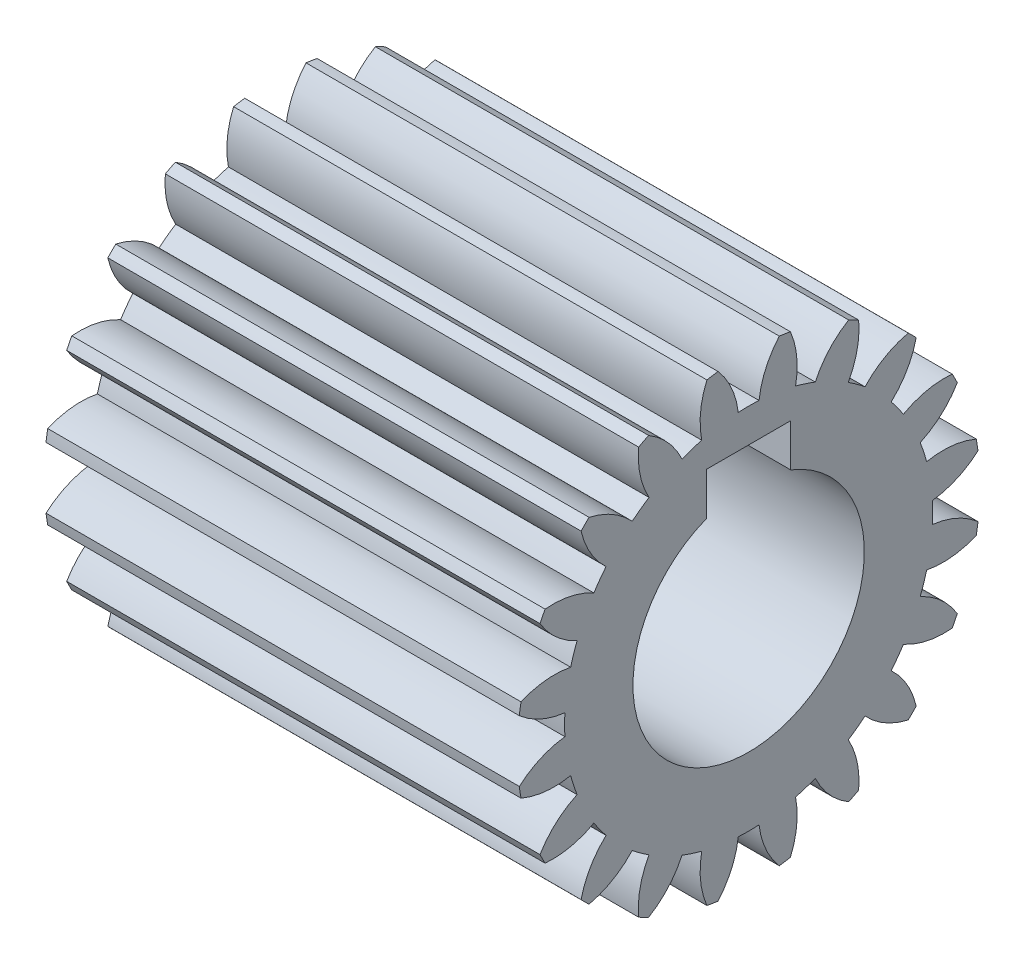
SolidWorks part; units mm, degrees
ref_plane "Plane1" through (0, 0, 0) normal (0, 0, 1) x (1, 0, 0)
ref_plane "Plane2" through (0, 0, 0) normal (0, 1, 0) x (1, 0, 0)
ref_plane "Plane3" through (0, 0, 0) normal (1, 0, 0) x (0, 0, -1)
sketch "HoldingSke" plane through (0, 0, 0) normal (0, 1, 0) x (1, 0, 0)
  line L0 (0, 0) -> (0.4698, -0.171)
  line L1 (-15, 0) -> (100, 0) construction
  line L2 (0, 0) -> (-2.1039, 2.3779)
  line L3 (0, 0) -> (-11.863, 4.5341)
  line L4 (0, 0) -> (8.1152, 2.9537)
  line L5 (0, 0) -> (-46.8476, -17.4728)
  line L6 (0, 0) -> (-37.3033, -25.1687)
  line L7 (-2.1039, 2.3779) -> (8.6586, 51.2059)
  line L8 (-76.2, 54.61) -> (-72.9, 54.61)
  line L9 (-71.009, 38.7566) -> (-53.1078, 45.2721)
  line L10 (-76.2, 71.12) -> (104.1128, 71.12)
  line L11 (0, 0) -> (-45, 0)
  line L12 (-76.2, 101.6) -> (-76.133, 101.6)
  line L13 (24.9733, 27.94) -> (52.9518, 28.4284)
  line L14 (24.9733, 27.94) -> (24.9743, 27.94)
  line L15 (24.9733, 27.94) -> (100.4006, 29.5858)
  line L16 (-63.627, -2) -> (-12.827, -2)
  circle A0 centre (0, 0) radius 11
  circle A1 centre (0, 0) radius 17.499
  circle A2 centre (0, 0) radius 37.5
  circle A3 centre (0, 0) radius 11
  dimension "MHD" = 34.998
  dimension "Hub_dia" = 75
  dimension "Bore" = 22
  dimension "MBD" = 22
  dimension "Num_teeth" = 20
  dimension "Pitch" = 0.5
  dimension "Overall_len" = 50
  dimension "Show_teeth" = 20
  dimension "Thickness" = 45
  dimension "OAL" = 50.0001
  dimension "T_dim" = 3.3
  dimension "Ap" = 20
  dimension "H" = 19.05
  dimension "Pitch_radius" = 180.3128
  dimension "Width" = 45
  dimension "Backlash" = 0.067
  dimension "Addendum_fac" = 1
  dimension "Dedendum_fac" = 1.25
  dimension "Clearance_fac" = 0.25
  dimension "Dedendum_add" = 0.001
  dimension "Module" = 2
sketch "BasProSke" plane through (0, 0, 0) normal (0, 1, 0) x (1, 0, 0)
  line L0 (-10, 0) -> (60, 0) construction
  line L1 (0, 0) -> (0, 22)
  line L2 (0, 0) -> (45, 0)
  line L3 (45, 0) -> (45, 22)
  line L4 (45, 22) -> (0, 22)
  dimension "Thickness" = 45
  dimension "Diameter" = 44
revolve "Base-Revolve" add sketch "BasProSke" angle 360 about L0
sketch "TooCutSke" plane through (0, 0, 0) normal (1, 0, 0) x (0, 0, -1)
  line L1 (0, 0) -> (0, 107) construction
  line L2 (0, 0) -> (-1.6864, 19.9288) construction
  line L3 (0, 0) -> (-6.2409, 39.4033) construction
  line L4 (-1.6864, 19.9288) -> (-3.1204, 19.7016) construction
  arc A0 (0.9862, 17.4712) -> (-0.9862, 17.4712) centre (0, 0) ccw
  arc A1 (2.9329, 21.8293) -> (-2.9329, 21.8293) centre (0, 0) ccw
  circle A2 centre (0, 0) radius 20 construction
  circle A3 centre (0, 0) radius 18.7939 construction
  arc A4 (-0.9862, 17.4712) -> (-2.9329, 21.8293) centre (-8.9313, 16.536) ccw
  arc A5 (2.9329, 21.8293) -> (0.9862, 17.4712) centre (8.9313, 16.536) ccw
  dimension "Root_dia" = 34.998
  dimension "Overcut_dia" = 44.0508
  dimension "Pitch_dia" = 40
  dimension "Base_dia" = 37.5877
  dimension "Flank_rad" = 8
  dimension "Half_ang" = 9
  dimension "Half_CT" = 1.4519
extrude "ToothCut" cut sketch "TooCutSke" along normal through all
fillet "Breaks" [suppressed] radius 0.04
fillet "RootFillets" [suppressed] radius 0.501
pattern_circular "TeethCuts" count 20 every 18 about axis through (-10, 0, 0) along (1, 0, 0) of "ToothCut", "RootFillets", "Breaks"
sketch "HubNeaOneSke" plane through (0, 0, 0) normal (-1, 0, 0) x (0, 0, 1)
  circle A0 centre (0, 0) radius 17.499
  dimension "Diameter" = 34.998
extrude "HubNearOne" [suppressed] add sketch "HubNeaOneSke" along normal blind 5.0001
sketch "HubNeaBotSke" plane through (0, 0, 0) normal (-1, 0, 0) x (0, 0, 1)
  circle A0 centre (0, 0) radius 17.499
  dimension "Diameter" = 34.998
extrude "HubNearBoth" [suppressed] add sketch "HubNeaBotSke" along normal blind 2.5
ref_plane "FarPln" through (45, 0, 0) normal (1, 0, 0) x (0, 0, -1)
sketch "HubFarSke" plane through (45, 0, 0) normal (1, 0, 0) x (0, 0, -1)
  circle A0 centre (0, 0) radius 17.499
  dimension "Diameter" = 34.998
extrude "HubFar" [suppressed] add sketch "HubFarSke" along normal blind 2.5
sketch "BorSke" plane through (0, 0, 0) normal (1, 0, 0) x (0, 0, -1)
  circle A0 centre (0, 0) radius 11
  dimension "Diameter" = 22
extrude "Bore" cut sketch "BorSke" along normal mid plane 100.0001
sketch "KeySke" plane through (0, 0, 0) normal (1, 0, 0) x (0, 0, -1)
  line L0 (-4, 0) -> (-4, 14.3)
  line L1 (-4, 14.3) -> (4, 14.3)
  line L2 (4, 14.3) -> (4, 0)
  line L3 (0, 0) -> (0, 34) construction
  line L4 (-4, 0) -> (4, 0)
  dimension "Offset" = 14.3
  dimension "Width" = 8
extrude "Keyway" cut sketch "KeySke" along normal mid plane 100.0001
pattern_circular "Keyway2" [suppressed] count 2 every 90 about axis through (-10, 0, 0) along (1, 0, 0)
equation "' \"Module@HoldingSke\" = 6.35"
equation "' \"Num_teeth@HoldingSke\" = 12"
equation "' \"Ap@HoldingSke\" =  20"
equation "' \"Ap@HoldingSke\" = 20"
equation "' \"Width@HoldingSke\" = 0.5 * 25.4"
equation "' \"Hub_dia@HoldingSke\"= 1 * 25.4"
equation "' \"Hub_dia@HoldingSke\" = 1 * 25.4"
equation "' \"Overall_len@HoldingSke\" = 1.0 * 25.4"
equation "' \"Bore@HoldingSke\" = 0.75 * 25.4"
equation "' \"T_dim@HoldingSke\" = 0.1 * 25.4"
equation "' \"Width@KeySke\" = 0.25 * 25.4"
equation "' \"Show_teeth@HoldingSke\" = 13"
equation "' \"Backlash@HoldingSke\" = 0.009 * 25.4"
equation "' \"Addendum_fac@HoldingSke\" = 1.0"
equation "' \"Dedendum_fac@HoldingSke\" = 1.25"
equation "' \"Dedendum_add@HoldingSke\" = 0.00005 * 25.4"
equation "' \"Clearance_fac@HoldingSke\" = 0.25"
equation "\"Pitch@HoldingSke\" = 1 / \"Module@HoldingSke\""
equation "\"Overcut_dia@TooCutSke\" = (\"Num_teeth@HoldingSke\" + 2 * \"Addendum_fac@HoldingSke\") / \"Pitch@HoldingSke\" + 0.002 * 25.4"
equation "\"Pitch_dia@TooCutSke\" = \"Num_teeth@HoldingSke\" / \"Pitch@HoldingSke\""
equation "\"Base_dia@TooCutSke\" = \"Num_teeth@HoldingSke\" / \"Pitch@HoldingSke\" * cos((\"Ap@HoldingSke\"  * 3.14159265 / 180))"
equation "\"Root_dia@TooCutSke\" = (\"Num_teeth@HoldingSke\" + 2) / \"Pitch@HoldingSke\" - 2 * (\"Addendum_fac@HoldingSke\" + \"Dedendum_fac@HoldingSke\") / \"Pitch@HoldingSke\" - \"Dedendum_add@HoldingSke\" * 2"
equation "\"Half_ang@TooCutSke\" = 180 / \"Num_teeth@HoldingSke\""
equation "\"Half_CT@TooCutSke\" = \"Num_teeth@HoldingSke\" / \"Pitch@HoldingSke\" * sin((3.14159265 / 2 / \"Num_teeth@HoldingSke\")) / 2 - 7 * \"Backlash@HoldingSke\" / 4"
equation "\"Flank_rad@TooCutSke\" = \"Num_teeth@HoldingSke\" / \"Pitch@HoldingSke\" / 5"
equation "\"Radius@RootFillets\" = \"Clearance_fac@HoldingSke\" / \"Pitch@HoldingSke\" + \"Dedendum_add@HoldingSke\""
equation "\"Break_rad@Breaks\" = 0.02 / \"Pitch@HoldingSke\""
equation "\"Thickness@HoldingSke\" = \"Width@HoldingSke\""
equation "\"OAL@HoldingSke\" = \"Thickness@HoldingSke\""
equation "\"MHD@HoldingSke\" = (\"Num_teeth@HoldingSke\" + 2) / \"Pitch@HoldingSke\" - 2 * (\"Addendum_fac@HoldingSke\" + \"Dedendum_fac@HoldingSke\")  / \"Pitch@HoldingSke\" - \"Dedendum_add@HoldingSke\" * 2"
equation "\"MBD@HoldingSke\" = (\"Num_teeth@HoldingSke\" + 2) / \"Pitch@HoldingSke\" - 2 * (\"Addendum_fac@HoldingSke\" + \"Dedendum_fac@HoldingSke\")  / \"Pitch@HoldingSke\" - \"Dedendum_add@HoldingSke\" * 2 - 0.002 * 25.4"
equation "\"MHD@HoldingSke\" = ((sgn( \"MHD@HoldingSke\" - \"Hub_dia@HoldingSke\" )-1)*( \"MHD@HoldingSke\" - \"Hub_dia@HoldingSke\" ))/-2+ \"Hub_dia@HoldingSke\""
equation "\"MBD@HoldingSke\" = ((sgn( \"MBD@HoldingSke\" - \"Bore@HoldingSke\" )-1)*( \"MBD@HoldingSke\" - \"Bore@HoldingSke\" ))/-2+ \"Bore@HoldingSke\""
equation "\"OAL@HoldingSke\" = ((sgn( \"OAL@HoldingSke\" - \"Overall_len@HoldingSke\" )+1)*( \"OAL@HoldingSke\" - \"Overall_len@HoldingSke\" ))/2 + \"Overall_len@HoldingSke\" + 0.000002 * 25.4"
equation "\"Num_teeth@TeethCuts\" = int( \"Show_teeth@HoldingSke\" ) + 1"
equation "\"Num_teeth@TeethCuts\" = ((sgn( \"Num_teeth@TeethCuts\" - \"Num_teeth@HoldingSke\" )-1)*( \"Num_teeth@TeethCuts\" - \"Num_teeth@HoldingSke\" ))/-2+ \"Num_teeth@HoldingSke\""
equation "\"Num_teeth@TeethCuts\" = ((sgn( \"Num_teeth@TeethCuts\" - 2.0)+1)*( \"Num_teeth@TeethCuts\" - 2.0))/2 +2.0"
equation "\"Angle@TeethCuts\" = 360.0 / \"Num_teeth@HoldingSke\""
equation "\"Diameter@BasProSke\" = (\"Num_teeth@HoldingSke\" + 2 * \"Addendum_fac@HoldingSke\") / \"Pitch@HoldingSke\""
equation "\"Thickness@BasProSke\"  = \"Thickness@HoldingSke\""
equation "' \"Fillet_rad@BasProSke\" =  \"Thickness@HoldingSke\" * 0.05"
equation "' \"Fillet_rad@BasProSke\" = \"Thickness@HoldingSke\" * 0.05"
equation "\"MHD@HoldingSke\" = ((sgn( \"MHD@HoldingSke\" - \"Root_dia@TooCutSke\" )-1)*( \"MHD@HoldingSke\" - \"Root_dia@TooCutSke\" ))/-2+ \"Root_dia@TooCutSke\""
equation "\"Diameter@HubNeaOneSke\" = \"MHD@HoldingSke\""
equation "\"Length@HubNearOne\" = \"OAL@HoldingSke\" - \"Thickness@BasProSke\""
equation "\"Diameter@HubNeaBotSke\" = \"MHD@HoldingSke\""
equation "\"Length@HubNearBoth\" = ( \"OAL@HoldingSke\" - \"Thickness@BasProSke\" ) / 2.0"
equation "\"Thickness@FarPln\" = \"Thickness@BasProSke\""
equation "\"Diameter@HubFarSke\" = \"MHD@HoldingSke\""
equation "\"Length@HubFar\" = ( \"OAL@HoldingSke\" - \"Thickness@BasProSke\" ) / 2.0"
equation "\"Diameter@BorSke\" = \"MBD@HoldingSke\""
equation "\"D1@Bore\" = \"OAL@HoldingSke\" * 2.0"
equation "\"D1@Keyway\" = \"OAL@HoldingSke\" * 2.0"
equation "\"Offset@KeySke\" = \"T_dim@HoldingSke\" + \"MBD@HoldingSke\" / 2.0"
